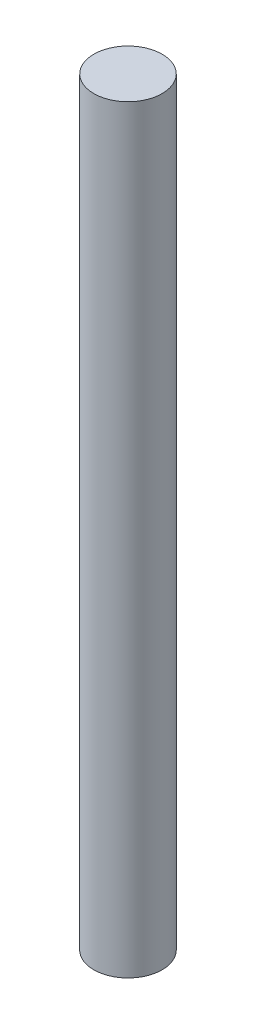
SolidWorks part; units mm, degrees
ref_plane "前视基准面" through (0, 0, 0) normal (0, 0, 1) x (1, 0, 0)
ref_plane "上视基准面" through (0, 0, 0) normal (0, 1, 0) x (1, 0, 0)
ref_plane "右视基准面" through (0, 0, 0) normal (1, 0, 0) x (0, 0, -1)
sketch "草图1" plane through (0, 0, 0) normal (0, 1, 0) x (1, 0, 0)
  circle A0 centre (0, 0) radius 2.25
  dimension "D1" = 4.5
extrude "凸台-拉伸1" add sketch "草图1" along normal blind 50
